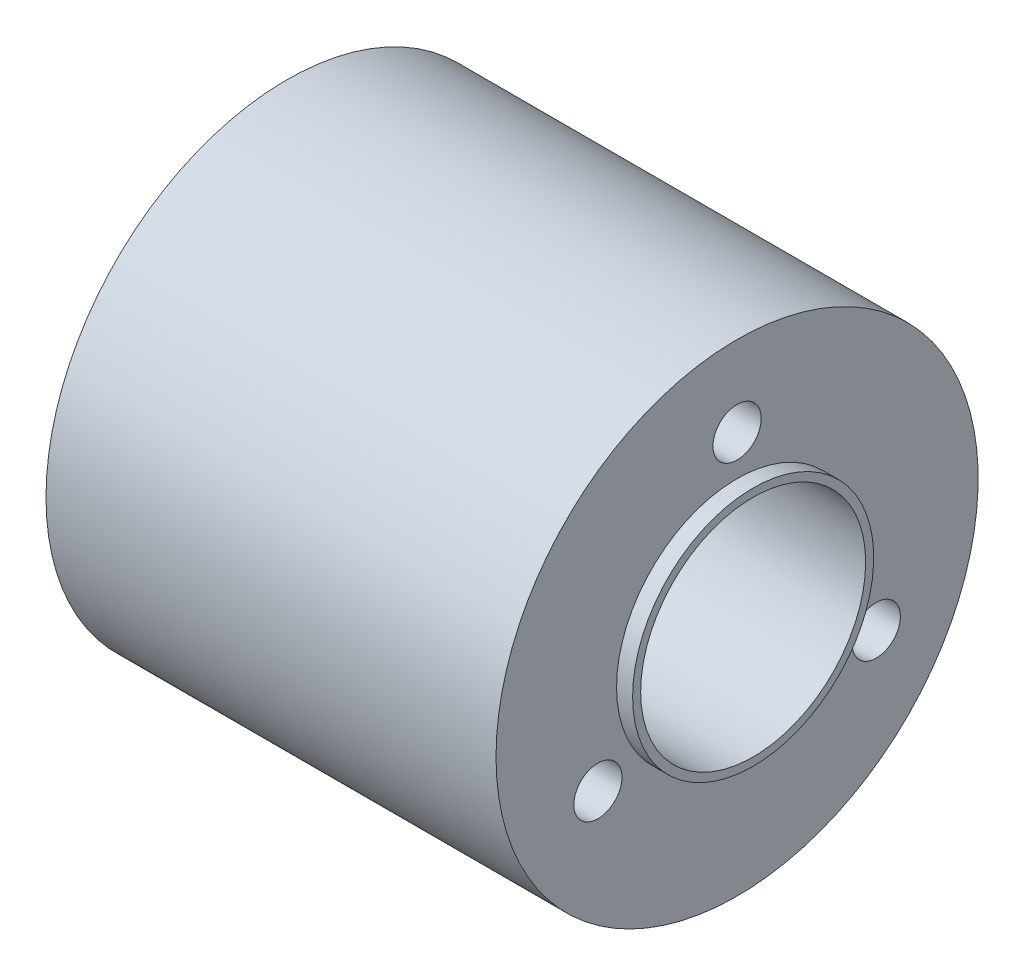
SolidWorks part; units mm, degrees
ref_plane "Front Plane" through (0, 0, 0) normal (0, 0, 1) x (1, 0, 0)
ref_plane "Top Plane" through (0, 0, 0) normal (0, 1, 0) x (1, 0, 0)
ref_plane "Right Plane" through (0, 0, 0) normal (1, 0, 0) x (0, 0, -1)
sketch "Sketch2" plane through (0, 0, 0) normal (0, 0, 1) x (1, 0, 0)
  line L0 (0, 0) -> (28, 0) construction
  line L1 (28, 0) -> (28, 15) construction
  line L2 (0, 0) -> (0, 15) construction
  line L3 (0, 15) -> (28, 15)
  line L4 (28, 15) -> (28, 7.5)
  line L5 (28, 7.5) -> (29, 7.5)
  line L6 (29, 7) -> (0, 7)
  line L7 (29, 7.5) -> (29, 7)
  line L8 (0, 15) -> (0, 7)
  line L9 (0, 7) -> (0, 15)
  dimension "D1" = 15
  dimension "D2" = 1
  dimension "D3" = 7
  dimension "D4" = 0.5
  dimension "D5" = 7.5
  dimension "D6" = 28
revolve "Revolve1" add sketch "Sketch2" angle 360 about L0
sketch "Sketch3" plane through (0, 0, 0) normal (-1, 0, 0) x (0, 0, 1)
  line L0 (0, 0) -> (0, 10) construction
  line L3 (0, 15) -> (0, 7.5) construction
  circle A2 centre (0, 10) radius 1.5
  dimension "D1" = 3
extrude "Cut-Extrude1" cut sketch "Sketch3" against normal up to next
pattern_circular "CirPattern1" count 3 over 360 about axis through (0, 0, 0) along (1, 0, 0) of "Cut-Extrude1"
